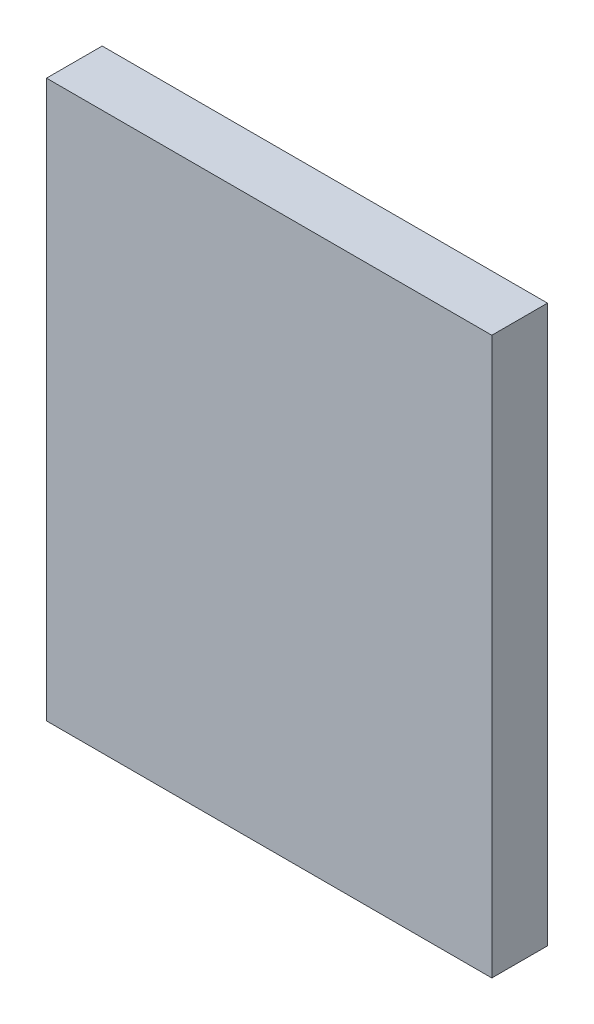
SolidWorks part; units mm, degrees
ref_plane "Front Plane" through (0, 0, 0) normal (0, 0, 1) x (1, 0, 0)
ref_plane "Top Plane" through (0, 0, 0) normal (0, 1, 0) x (1, 0, 0)
ref_plane "Right Plane" through (0, 0, 0) normal (1, 0, 0) x (0, 0, -1)
sketch "Sketch1" plane through (0, 0, 0) normal (0, 1, 0) x (1, 0, 0)
  line L1 (101.6, -12.7) -> (-101.6, -12.7)
  line L2 (101.6, -12.7) -> (101.6, 12.7)
  line L3 (101.6, 12.7) -> (-101.6, 12.7)
  line L4 (-101.6, -12.7) -> (-101.6, 12.7)
  line L5 (101.6, -12.7) -> (-101.6, 12.7) construction
  line L6 (101.6, 12.7) -> (-101.6, -12.7) construction
  point P0 (0, 0)
  point P5 (-22.3437, -42.2986)
  point P6 (0, 0)
  dimension "D1" = 25.4
  dimension "D2" = 203.2
extrude "Boss-Extrude1" add sketch "Sketch1" along normal blind 254 contours L3 L4 L1 L2
